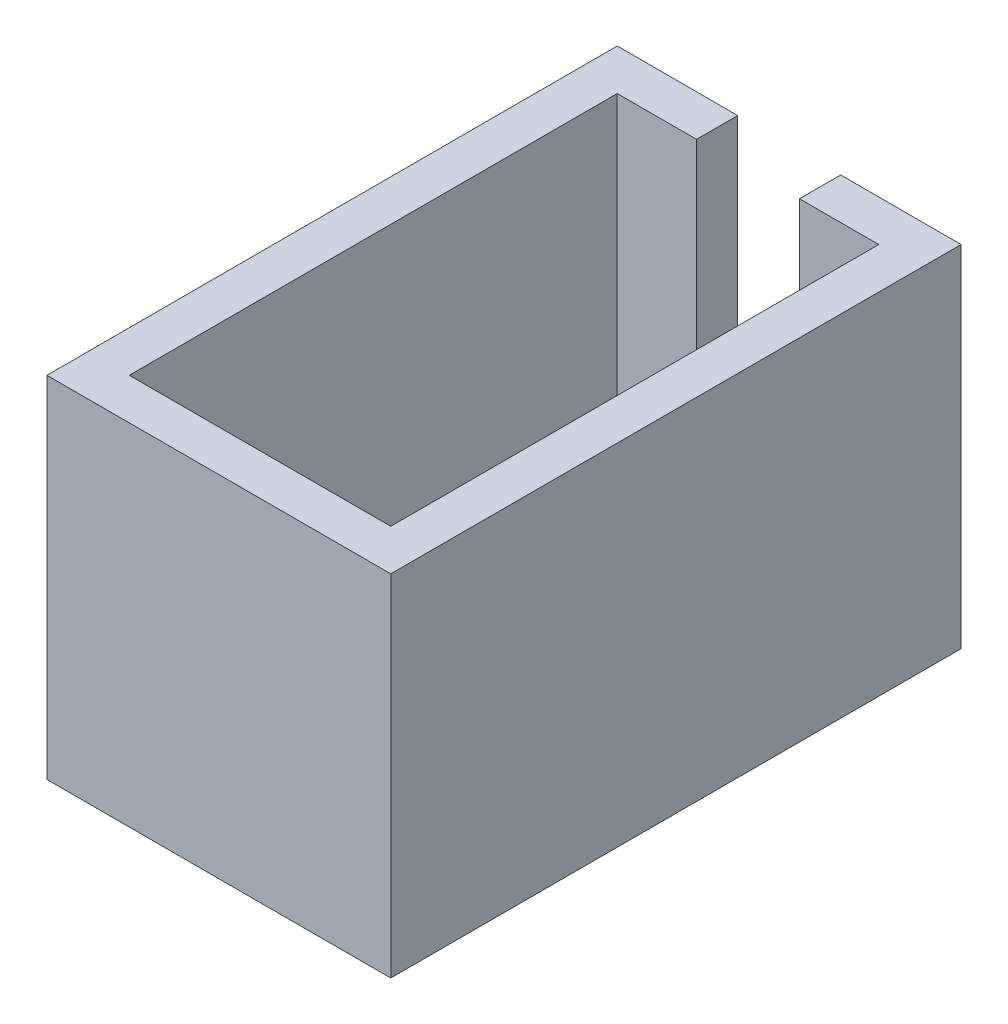
SolidWorks part; units mm, degrees
ref_plane "Front Plane" through (0, 0, 0) normal (0, 0, 1) x (1, 0, 0)
ref_plane "Top Plane" through (0, 0, 0) normal (0, 1, 0) x (1, 0, 0)
ref_plane "Right Plane" through (0, 0, 0) normal (1, 0, 0) x (0, 0, -1)
sketch "Sketch1" plane through (0, 0, 0) normal (0, 1, 0) x (1, 0, 0)
  line L1 (0, 0) -> (12.7, 0)
  line L2 (0, 0) -> (0, 23.7)
  line L3 (0, 23.7) -> (12.7, 23.7)
  line L4 (12.7, 0) -> (12.7, 23.7)
  dimension "D1" = 12.7
  dimension "D2" = 23.7
extrude "Boss-Extrude1" add sketch "Sketch1" along normal blind 2
sketch "Sketch2" plane through (0, 0, 0) normal (0, 0, 1) x (1, 0, 0)
  line L1 (0, 0) -> (12.7, 0)
  line L2 (0, 0) -> (0, 17)
  line L3 (0, 17) -> (12.7, 17)
  line L4 (12.7, 0) -> (12.7, 17)
  dimension "D1" = 17
extrude "Boss-Extrude2" add sketch "Sketch2" along normal blind 2
sketch "Sketch3" plane through (0, 0, -23.7) normal (0, 0, -1) x (-1, 0, 0)
  line L1 (-12.7, 0) -> (0, 0)
  line L2 (-12.7, 0) -> (-12.7, 17)
  line L3 (-12.7, 17) -> (0, 17)
  line L4 (0, 0) -> (0, 17)
  dimension "D1" = 17
extrude "Boss-Extrude3" add sketch "Sketch3" along normal blind 2
sketch "Sketch4" plane through (12.7, 0, 0) normal (1, 0, 0) x (0, 0, -1)
  line L1 (-2, 0) -> (25.7, 0)
  line L2 (-2, 0) -> (-2, 17)
  line L3 (-2, 17) -> (25.7, 17)
  line L4 (25.7, 0) -> (25.7, 17)
extrude "Boss-Extrude4" add sketch "Sketch4" along normal blind 2
sketch "Sketch5" plane through (0, 0, 0) normal (-1, 0, 0) x (0, 0, 1)
  line L1 (-25.7, 0) -> (2, 0)
  line L2 (-25.7, 0) -> (-25.7, 17)
  line L3 (-25.7, 17) -> (2, 17)
  line L4 (2, 0) -> (2, 17)
extrude "Boss-Extrude5" add sketch "Sketch5" along normal blind 2
sketch "Sketch7" plane through (0, 0, -23.7) normal (0, 0, 1) x (1, 0, 0)
  line L0 (0, 17) -> (12.7, 17) construction
  line L1 (3.85, 17) -> (8.85, 17)
  line L2 (3.85, 17) -> (3.85, 4.5)
  line L3 (3.85, 4.5) -> (8.85, 4.5)
  line L4 (8.85, 17) -> (8.85, 4.5)
  line L6 (12.7, 2) -> (0, 2) construction
  line L7 (12.7, 17) -> (12.7, 2) construction
  dimension "D2" = 5
  dimension "D3" = 2.5
  dimension "D1" = 3.85
extrude "Cut-Extrude2" cut sketch "Sketch7" against normal up to next
equation "\"D1@Sketch7\"=(\"RD1@Annotations\"-\"D2@Sketch7\")/2"
